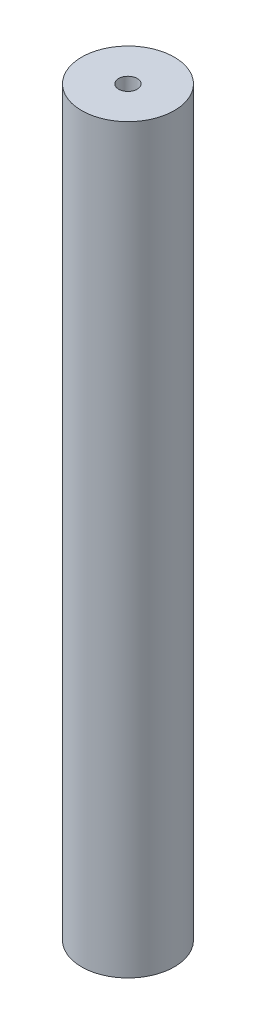
SolidWorks part; units mm, degrees
material "6061-T6 (SS)"
ref_plane "Front Plane" through (0, 0, 0) normal (0, 0, 1) x (1, 0, 0)
ref_plane "Top Plane" through (0, 0, 0) normal (0, 1, 0) x (1, 0, 0)
ref_plane "Right Plane" through (0, 0, 0) normal (1, 0, 0) x (0, 0, -1)
sketch "Sketch1" plane through (0, 0, 0) normal (0, 1, 0) x (1, 0, 0)
  circle A0 centre (0, 0) radius 12.7
  dimension "D1" = 25.4
extrude "Boss-Extrude1" add sketch "Sketch1" along normal mid plane 203.2
hole_wizard "1/4-20 Tapped Hole1" positions "3DSketch1" profile "Sketch2" tap size "1/4-20" standard "ANSI Inch"
sketch3d "3DSketch1"
  line L0 (0, 101.6, 0) -> (0, -101.6, 0) construction
  point P0 (0, 101.6, 0)
  point P4 (0, -101.6, 0)
sketch "Sketch2" plane through (0, 101.6, 0) normal (1, 0, 0) x (0, 0, 1)
  line L0 (0, 0) -> (0, 18.0438)
  line L1 (0, 18.0438) -> (2.5527, 16.51)
  line L2 (2.5527, 16.51) -> (2.5527, 0)
  line L5 (2.5527, 0) -> (0, 0)
  line L10 (0, 18.0438) -> (-2.5527, 16.51) construction
  line L11 (0, -6.35) -> (0, 107.95) construction
  dimension "Tap Drill Dia." = 5.1054
  dimension "Tap Drill Depth" = 16.51
  dimension "Drill Angle" = 118
cosmetic thread "Hole Thread1" parameters "D1"=12.7, "D2"=6.35
cosmetic thread "Hole Thread2" parameters "D1"=12.7, "D2"=6.35
